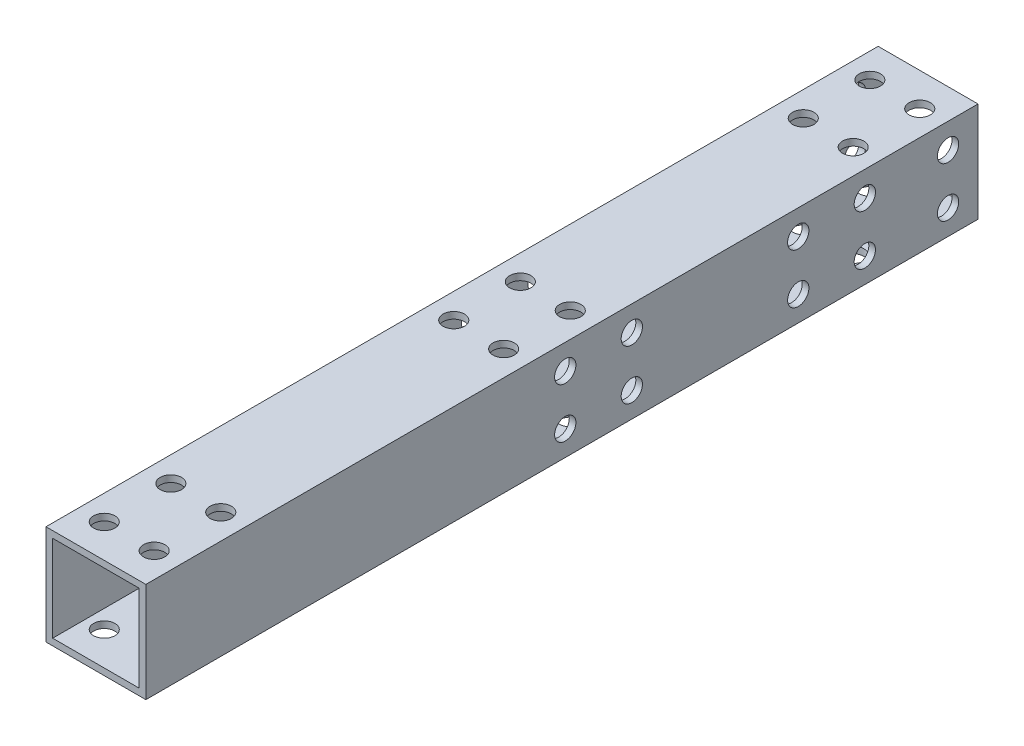
SolidWorks part; units mm, degrees
ref_plane "前视基准面" through (0, 0, 0) normal (0, 0, 1) x (1, 0, 0)
ref_plane "上视基准面" through (0, 0, 0) normal (0, 1, 0) x (1, 0, 0)
ref_plane "右视基准面" through (0, 0, 0) normal (1, 0, 0) x (0, 0, -1)
other "Configuration Table"
sketch "草图1" plane through (0, 0, 0) normal (0, 0, 1) x (1, 0, 0)
  line L1 (0, 0) -> (15, 0)
  line L2 (0, 0) -> (0, -15)
  line L3 (0, -15) -> (15, -15)
  line L4 (15, 0) -> (15, -15)
  dimension "D1" = 15
  dimension "D2" = 15
extrude "拉伸-薄壁1" add sketch "草图1" along normal blind 125 thin
sketch "草图2" plane through (15, 0, 0) normal (1, 0, 0) x (0, 0, -1)
  line L1 (-125, 0) -> (0, 0) construction
  line L2 (-125, -15) -> (0, -15) construction
  line L3 (-57, 0) -> (-57, -15) construction
  line L4 (-125, -15) -> (-125, 0) construction
  line L5 (-125, -7.5) -> (-57, -7.5) construction
  line L6 (-22, 0) -> (-22, -15) construction
  line L7 (0, -7.5) -> (-22, -7.5) construction
  line L8 (0, -15) -> (0, 0) construction
  line L9 (-22, -7.5) -> (-57, -7.5) construction
  circle A0 centre (-62, -3.75) radius 1.6
  circle A1 centre (-62, -11.25) radius 1.6
  circle A2 centre (-52, -11.25) radius 1.6
  circle A3 centre (-52, -3.75) radius 1.6
  circle A8 centre (-17, -3.75) radius 1.6
  circle A9 centre (-17, -11.25) radius 1.6
  circle A10 centre (-27, -11.25) radius 1.6
  circle A11 centre (-27, -3.75) radius 1.6
  circle A13 centre (-4.5, -3.75) radius 1.6
  circle A14 centre (-4.5, -11.25) radius 1.6
  point P36 (-34.2695, -7.5)
  dimension "D2" = 3.2
  dimension "D6" = 3.2
  dimension "D11" = 3.2
  dimension "D1" = 68
  dimension "D3" = 5
  dimension "D4" = 3.75
  dimension "D5" = 35
  dimension "D7" = 3.75
  dimension "D8" = 5
  dimension "D12" = 17.5
  dimension "D13" = 3.75
extrude "切除-拉伸1" cut sketch "草图2" against normal through all
sketch "草图3" plane through (0, 0, 0) normal (0, 1, 0) x (1, 0, 0)
  line L0 (7.5, 0) -> (7.5, -125) construction
  line L1 (15, 0) -> (0, 0) construction
  line L2 (15, -125) -> (0, -125) construction
  line L3 (15, -62.5) -> (0, -62.5) construction
  line L4 (15, -125) -> (15, 0) construction
  line L5 (0, -125) -> (0, 0) construction
  line L6 (0, -10) -> (15, -10) construction
  line L7 (0, -115) -> (15, -115) construction
  circle A0 centre (3.75, -5) radius 1.6
  circle A1 centre (11.25, -5) radius 1.6
  circle A2 centre (11.25, -15) radius 1.6
  circle A3 centre (3.75, -15) radius 1.6
  circle A16 centre (3.75, -57.5) radius 1.6
  circle A17 centre (11.25, -57.5) radius 1.6
  circle A18 centre (11.25, -67.5) radius 1.6
  circle A19 centre (3.75, -67.5) radius 1.6
  circle A28 centre (3.75, -110) radius 1.6
  circle A29 centre (11.25, -110) radius 1.6
  circle A30 centre (11.25, -120) radius 1.6
  circle A31 centre (3.75, -120) radius 1.6
  dimension "D1" = 3.2
  dimension "D7" = 3.2
  dimension "D2" = 3.75
  dimension "D3" = 10
  dimension "D4" = 5
  dimension "D8" = 5
  dimension "D9" = 3.75
extrude "切除-拉伸2" cut sketch "草图3" against normal through all
